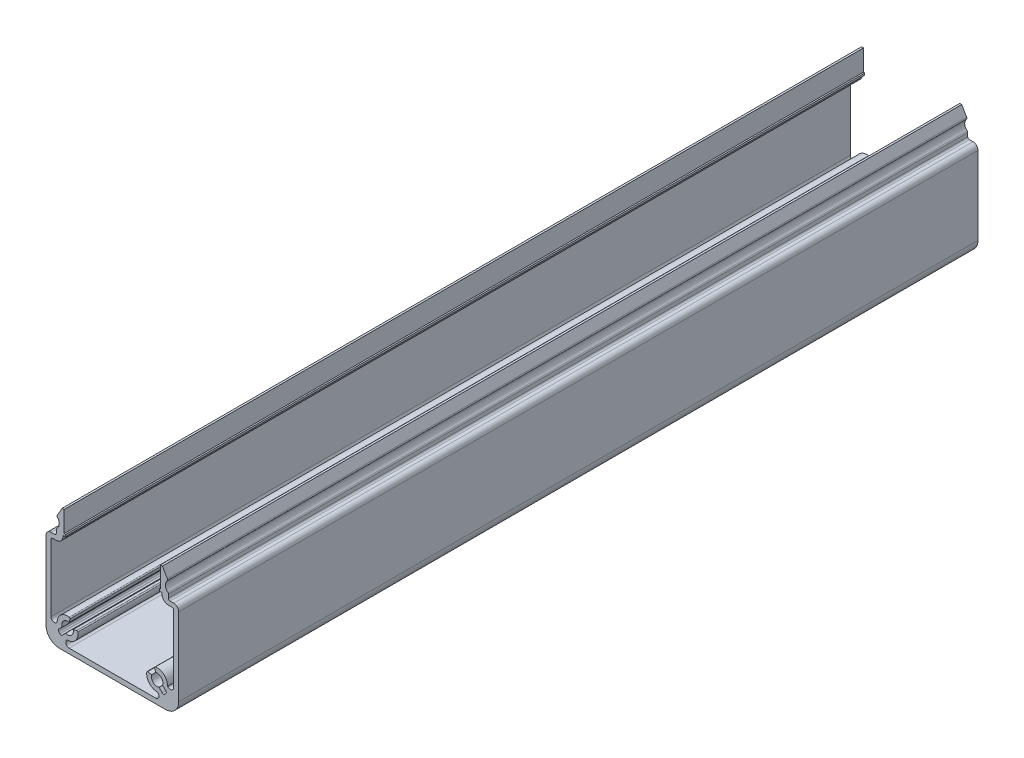
SolidWorks part; units mm, degrees
ref_plane "Front Plane" through (0, 0, 0) normal (0, 0, 1) x (1, 0, 0)
ref_plane "Top Plane" through (0, 0, 0) normal (0, 1, 0) x (1, 0, 0)
ref_plane "Right Plane" through (0, 0, 0) normal (1, 0, 0) x (0, 0, -1)
ref_plane "Plane1" through (0, 0, 20) normal (0, 0, 1) x (1, 0, 0)
sketch "Sketch1" plane through (0, 0, 20) normal (0, 0, 1) x (1, 0, 0)
  line L0 (4, 0) -> (36, 0)
  line L1 (40, 4) -> (40, 27.5)
  line L2 (38.5, 29) -> (37.4085, 29)
  line L3 (36.9085, 29.5) -> (36.9085, 30.572)
  line L4 (36.583, 34.4315) -> (35.1, 37)
  line L5 (35.1, 37) -> (34.5, 37)
  line L6 (34.5, 37) -> (34.5, 30.6727)
  line L7 (34.5, 30.6727) -> (34.1585, 30.5611)
  line L8 (34.1585, 30.5611) -> (34.1585, 29.9899)
  line L9 (34.1585, 29.9899) -> (34.9085, 29.9899)
  line L10 (34.9085, 29.9899) -> (34.9085, 29.7)
  line L11 (36.9085, 27.7) -> (38, 27.7)
  line L12 (38.5, 27.2) -> (38.5, 6.9548)
  line L13 (36.7929, 6.2477) -> (36.6482, 6.3924)
  line L14 (32.7665, 9.2376) -> (33.0471, 8.1904)
  line L15 (35.1484, 5.9123) -> (36.1464, 4.9142)
  line L16 (36.1464, 4.2071) -> (35.7929, 3.8536)
  line L17 (35.0858, 3.8536) -> (34.0877, 4.8516)
  line L18 (31.8096, 6.9529) -> (30.7624, 7.2335)
  line L19 (33.6076, 3.3518) -> (33.7523, 3.2071)
  line L20 (33.0452, 1.5) -> (6.9548, 1.5)
  line L21 (6.2477, 3.2071) -> (6.3924, 3.3518)
  line L22 (9.2376, 7.2335) -> (8.1904, 6.9529)
  line L23 (5.9123, 4.8516) -> (4.9142, 3.8536)
  line L24 (4.2071, 3.8536) -> (3.8536, 4.2071)
  line L25 (3.8536, 4.9142) -> (4.8516, 5.9123)
  line L26 (6.9529, 8.1904) -> (7.2335, 9.2376)
  line L27 (3.3518, 6.3924) -> (3.2071, 6.2477)
  line L28 (1.5, 6.9548) -> (1.5, 27.2)
  line L29 (2, 27.7) -> (3.0915, 27.7)
  line L30 (5.0915, 29.7) -> (5.0915, 29.9899)
  line L31 (5.0915, 29.9899) -> (5.8415, 29.9899)
  line L32 (5.8415, 29.9899) -> (5.8415, 30.5611)
  line L33 (5.8415, 30.5611) -> (5.5, 30.6727)
  line L34 (5.5, 30.6727) -> (5.5, 37)
  line L35 (5.5, 37) -> (4.9, 37)
  line L36 (4.9, 37) -> (3.417, 34.4315)
  line L37 (3.0915, 30.572) -> (3.0915, 29.5)
  line L38 (2.5915, 29) -> (1.5, 29)
  line L39 (0, 27.5) -> (0, 4)
  arc A0 (36, 0) -> (40, 4) centre (36, 4) ccw
  arc A1 (40, 27.5) -> (38.5, 29) centre (38.5, 27.5) ccw
  arc A2 (37.4085, 29) -> (36.9085, 29.5) centre (37.4085, 29.5) cw
  arc A3 (36.9085, 30.572) -> (36.7268, 30.9576) centre (36.4085, 30.572) ccw
  arc A4 (36.7268, 30.9576) -> (36.52, 33.8452) centre (38, 32.5) cw
  arc A5 (36.52, 33.8452) -> (36.583, 34.4315) centre (36.1499, 34.1815) ccw
  arc A6 (34.9085, 29.7) -> (36.9085, 27.7) centre (36.9085, 29.7) ccw
  arc A7 (38, 27.7) -> (38.5, 27.2) centre (38, 27.2) cw
  arc A8 (38.5, 6.9548) -> (36.7929, 6.2477) centre (37.5, 6.9548) cw
  arc A9 (36.6482, 6.3924) -> (33.0095, 9.6116) centre (33.5, 6.5) ccw
  arc A10 (33.0095, 9.6116) -> (32.7665, 9.2376) centre (33.0562, 9.3152) ccw
  arc A11 (33.0471, 8.1904) -> (35.1484, 5.9123) centre (33.5, 6.5) cw
  arc A12 (36.1464, 4.9142) -> (36.1464, 4.2071) centre (35.7929, 4.5607) cw
  arc A13 (35.7929, 3.8536) -> (35.0858, 3.8536) centre (35.4393, 4.2071) cw
  arc A14 (34.0877, 4.8516) -> (31.8096, 6.9529) centre (33.5, 6.5) cw
  arc A15 (30.7624, 7.2335) -> (30.3884, 6.9905) centre (30.6848, 6.9438) ccw
  arc A16 (30.3884, 6.9905) -> (33.6076, 3.3518) centre (33.5, 6.5) ccw
  arc A17 (33.7523, 3.2071) -> (33.0452, 1.5) centre (33.0452, 2.5) cw
  arc A18 (6.9548, 1.5) -> (6.2477, 3.2071) centre (6.9548, 2.5) cw
  arc A19 (6.3924, 3.3518) -> (9.6116, 6.9905) centre (6.5, 6.5) ccw
  arc A20 (9.6116, 6.9905) -> (9.2376, 7.2335) centre (9.3152, 6.9438) ccw
  arc A21 (8.1904, 6.9529) -> (5.9123, 4.8516) centre (6.5, 6.5) cw
  arc A22 (4.9142, 3.8536) -> (4.2071, 3.8536) centre (4.5607, 4.2071) cw
  arc A23 (3.8536, 4.2071) -> (3.8536, 4.9142) centre (4.2071, 4.5607) cw
  arc A24 (4.8516, 5.9123) -> (6.9529, 8.1904) centre (6.5, 6.5) cw
  arc A25 (7.2335, 9.2376) -> (6.9905, 9.6116) centre (6.9438, 9.3152) ccw
  arc A26 (6.9905, 9.6116) -> (3.3518, 6.3924) centre (6.5, 6.5) ccw
  arc A27 (3.2071, 6.2477) -> (1.5, 6.9548) centre (2.5, 6.9548) cw
  arc A28 (1.5, 27.2) -> (2, 27.7) centre (2, 27.2) cw
  arc A29 (3.0915, 27.7) -> (5.0915, 29.7) centre (3.0915, 29.7) ccw
  arc A30 (3.417, 34.4315) -> (3.48, 33.8452) centre (3.8501, 34.1815) ccw
  arc A31 (3.48, 33.8452) -> (3.2732, 30.9576) centre (2, 32.5) cw
  arc A32 (3.2732, 30.9576) -> (3.0915, 30.572) centre (3.5915, 30.572) ccw
  arc A33 (3.0915, 29.5) -> (2.5915, 29) centre (2.5915, 29.5) cw
  arc A34 (1.5, 29) -> (0, 27.5) centre (1.5, 27.5) ccw
  arc A35 (0, 4) -> (4, 0) centre (4, 4) ccw
extrude "Boss-Extrude1" add sketch "Sketch1" against normal blind 241
